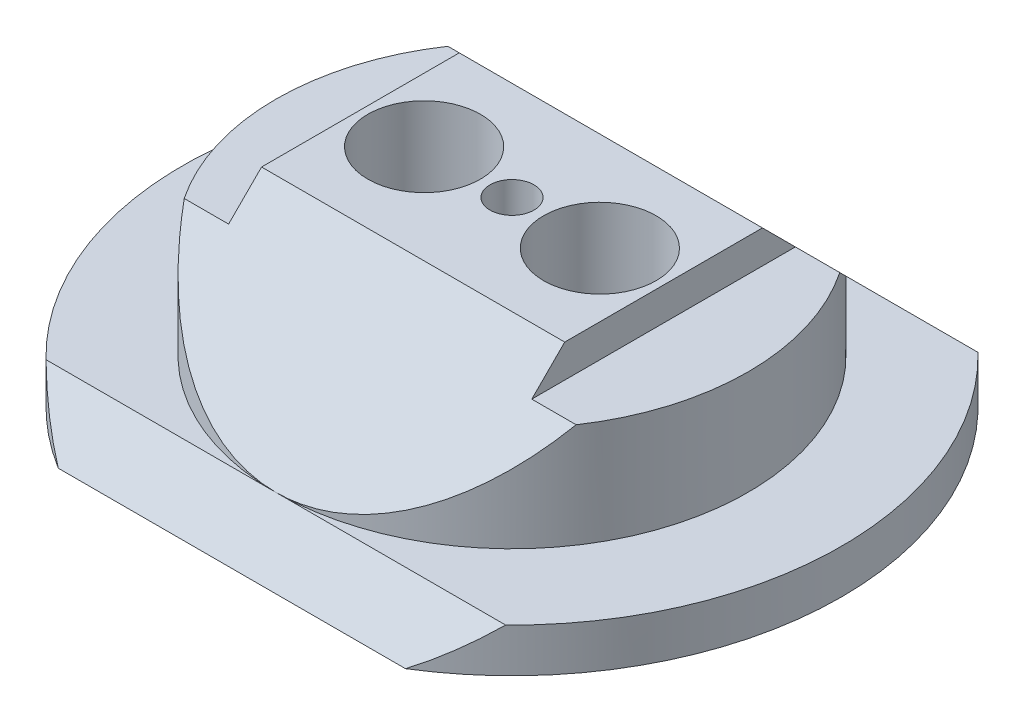
SolidWorks part; units mm, degrees
ref_plane "Front Plane" through (0, 0, 0) normal (0, 0, 1) x (1, 0, 0)
ref_plane "Top Plane" through (0, 0, 0) normal (0, 1, 0) x (1, 0, 0)
ref_plane "Right Plane" through (0, 0, 0) normal (1, 0, 0) x (0, 0, -1)
sketch "Sketch1" plane through (0, 0, 0) normal (0, 1, 0) x (1, 0, 0)
  circle A0 centre (0, 0) radius 30
extrude "Boss-Extrude1" add sketch "Sketch1" along normal blind 4
sketch "Sketch2" plane through (0, 0, 0) normal (1, 0, 0) x (0, 0, -1)
  line L0 (0, 4) -> (21.5, 4)
  line L1 (30, 4) -> (-30, 4) construction
  line L3 (0, 4) -> (-21.5, 4)
  line L5 (0, 4) -> (0, 19.5) construction
  line L6 (-9, 16.5) -> (-21.5, 4)
  line L7 (-9, 16.5) -> (9, 16.5)
  line L9 (9, 16.5) -> (21.5, 4)
  dimension "D1" = 12.5
  dimension "D2" = 45
  dimension "D3" = 21.5
  dimension "D4" = 21.5
  dimension "D5" = 45
sketch "Sketch3" plane through (0, 4, 0) normal (0, 1, 0) x (1, 0, 0)
  circle A0 centre (0, 0) radius 21.5
  dimension "D1" = 43
extrude "Boss-Extrude2" add sketch "Sketch2" along normal up to surface and the other way up to surface up to face at (0, 4, 30) other way up to face at (0, 4, 30)
ref_plane "Plane1" through (0, 12.75, -12.75) normal (0, 0.7071, -0.7071) x (1, 0, 0)
other "SurfaceCut1"
ref_plane "Plane2" through (0, 12.75, 12.75) normal (0, 0.7071, 0.7071) x (1, 0, 0)
other "SurfaceCut2"
extrude "Cut-Extrude2" cut sketch "Sketch3" against normal up to surface (12.5 mm away) flip side to cut contours A0
sketch "Sketch5" plane through (0, 0, 0) normal (0, -1, 0) x (-1, 0, 0)
  line L0 (0, 0) -> (0, -6)
  line L1 (0, -6) -> (-17.5, -6)
  line L2 (-17.5, -6) -> (-17.5, 6)
  line L3 (-17.5, 6) -> (17.5, 6)
  line L4 (17.5, 6) -> (17.5, -6)
  line L5 (17.5, -6) -> (0, -6)
  circle A0 centre (0, 0) radius 6
  circle A1 centre (0, 0) radius 3.5
  dimension "D1" = 12
  dimension "D2" = 7
  dimension "D3" = 12
  dimension "D4" = 6
  dimension "D5" = 35
  dimension "D6" = 17.5
extrude "Boss-Extrude3" add sketch "Sketch5" along normal blind 18 contours L1 L2 L3 L4 L5
sketch "Sketch6" plane through (0, 0, 0) normal (0, -1, 0) x (1, 0, 0)
  line L0 (0, 6) -> (0, 15) construction
  line L1 (-17.5, 6) -> (17.5, 6) construction
  line L2 (0, 15) -> (7, 15)
  line L3 (7, 15) -> (7, 6)
  line L4 (-17.5, 6) -> (17.5, 6) construction
  line L5 (7, 6) -> (-7, 6)
  line L6 (-7, 6) -> (-7, 15)
  line L7 (-7, 15) -> (0, 15)
  dimension "D1" = 14
  dimension "D2" = 9
extrude "Boss-Extrude4" add sketch "Sketch6" along normal blind 15 contours L7 L2 L3 L5 L6
sketch "Sketch7" plane through (0, 0, 0) normal (0, -1, 0) x (1, 0, 0)
  line L0 (0, -6) -> (0, -15) construction
  line L1 (17.5, -6) -> (-17.5, -6) construction
  line L2 (0, -15) -> (7, -15)
  line L3 (7, -15) -> (7, -6)
  line L4 (7, -6) -> (-7, -6)
  line L7 (-7, -6) -> (-7, -15)
  line L8 (-7, -15) -> (0, -15)
  dimension "D1" = 9
  dimension "D2" = 14
extrude "Boss-Extrude5" add sketch "Sketch7" along normal blind 15
sketch "Sketch8" plane through (0, 0, 0) normal (0, 0, 1) x (1, 0, 0)
  line L0 (0, 0) -> (12.5, 0) construction
  line L1 (12.5, 0) -> (12.5, -12.5) construction
  line L2 (12.5, -12.5) -> (-12.5, -12.5) construction
  line L3 (-12.5, -12.5) -> (-12.5, 0) construction
  line L4 (-12.5, 0) -> (0, 0) construction
  circle A0 centre (-12.5, -12.5) radius 2
  circle A1 centre (12.5, -12.5) radius 2
  dimension "D4" = 4
  dimension "D5" = 4
  dimension "D1" = 12.5
  dimension "D2" = 25
  dimension "D3" = 12.5
extrude "Cut-Extrude3" cut sketch "Sketch8" against normal through all both and the other way through all contours A0 | A1
ref_plane "Plane3" through (0, -18, 0) normal (0, -1, 0) x (-1, 0, 0)
ref_plane "Plane4" through (10.366, -9.6749, -8.0624) normal (0.6355, -0.5931, -0.4943) x (-0.3613, 0.3373, -0.8693)
ref_plane "Plane5" through (-10.366, -9.6749, -8.0624) normal (0.6355, 0.5931, 0.4943) x (0.3613, 0.3373, -0.8693)
ref_plane "Plane6" through (10.366, -9.6749, 8.0624) normal (-0.6355, 0.5931, -0.4943) x (-0.3613, 0.3373, 0.8693)
ref_plane "Plane7" through (-10.366, -9.6749, 8.0624) normal (0.6355, 0.5931, -0.4943) x (-0.3613, -0.3373, -0.8693)
ref_plane "Plane9" through (0, 0, 6) normal (0, 0, 1) x (1, 0, 0)
sketch "Sketch16" plane through (0, 0, 6) normal (0, 0, 1) x (1, 0, 0)
  line L0 (17.5, -18) -> (17.5, -14.5)
  line L1 (-6.6, -18) -> (6.6, -18) construction
  line L2 (17.5, -18) -> (17.5, 0) construction
  line L3 (17.5, -18) -> (14, -18)
  line L4 (17.5, -14.5) -> (14, -18)
  line L5 (-17.5, -18) -> (-14, -18)
  line L6 (-17.5, -18) -> (-17.5, 0) construction
  line L7 (-14, -18) -> (-17.5, -14.5)
  line L8 (-17.5, -14.5) -> (-17.5, -18)
  dimension "D2" = 3.5
extrude "Cut-Extrude8" cut sketch "Sketch16" against normal through all both and the other way through all
sketch "Sketch17" plane through (10.366, -9.6749, -8.0624) normal (0.6355, -0.5931, -0.4943) x (-0.3613, 0.3373, -0.8693)
  line L0 (-2.3725, -6.1896) -> (7.9806, -0.7067)
  line L1 (5.4512, -6.1896) -> (10.5101, 4.7762) construction
  line L2 (7.9806, -0.7067) -> (7.9806, -10.9658)
  line L3 (10.5101, -15.7421) -> (5.4512, -6.1896) construction
  line L4 (7.9806, -10.9658) -> (-2.3725, -6.1896)
extrude "Cut-Extrude9" cut sketch "Sketch17" along normal through all
sketch "Sketch19" plane through (-10.366, -9.6749, -8.0624) normal (0.6355, 0.5931, 0.4943) x (0.3613, 0.3373, -0.8693)
  line L0 (-2.3725, -6.1896) -> (7.9806, -10.9658)
  line L1 (7.9806, -10.9658) -> (7.9806, -0.7067)
  line L2 (5.4512, -6.1896) -> (10.5101, 4.7762) construction
  line L3 (7.9806, -0.7067) -> (-2.3725, -6.1896)
extrude "Cut-Extrude11" cut sketch "Sketch19" against normal blind 20 contours L3 L0 L1
sketch "Sketch20" plane through (-10.366, -9.6749, 8.0624) normal (0.6355, 0.5931, -0.4943) x (-0.3613, -0.3373, -0.8693)
  line L0 (2.3725, -6.1896) -> (-7.9806, -0.7067)
  line L1 (-5.4512, -6.1896) -> (-10.5101, 4.7762) construction
  line L2 (-7.9806, -0.7067) -> (-7.9806, -10.9658)
  line L3 (-5.4512, -6.1896) -> (-10.5101, -15.7421) construction
  line L4 (-7.9806, -10.9658) -> (2.3725, -6.1896)
extrude "Cut-Extrude12" cut sketch "Sketch20" against normal blind 20
sketch "Sketch21" plane through (10.366, -9.6749, 8.0624) normal (-0.6355, 0.5931, -0.4943) x (-0.3613, 0.3373, 0.8693)
  line L0 (-2.3725, -6.1896) -> (7.9806, -0.7067)
  line L1 (5.4512, -6.1896) -> (10.5101, 4.7762) construction
  line L2 (7.9806, -0.7067) -> (7.9806, -10.9658)
  line L3 (7.9806, -10.9658) -> (-2.3725, -6.1896)
extrude "Cut-Extrude13" cut sketch "Sketch21" against normal blind 20 contours L0 L2 L3
ref_plane "Plane10" through (0, 16.5, 0) normal (0, 1, 0) x (1, 0, 0)
sketch "Sketch25" plane through (0, 0, 0) normal (0, 0, 1) x (1, 0, 0)
  line L1 (-33.0377, 0) -> (33.0377, 0)
  line L2 (-33.0377, 0) -> (-33.0377, -20.1422)
  line L3 (-33.0377, -20.1422) -> (33.0377, -20.1422)
  line L4 (33.0377, 0) -> (33.0377, -20.1422)
  dimension "D1" = 20.1422
  dimension "D2" = 66.0754
extrude "Cut-Extrude14" cut sketch "Sketch25" along normal through all both and the other way through all
sketch "Sketch26" plane through (0, 16.5, 0) normal (0, 1, 0) x (1, 0, 0)
  line L0 (-9.075, 0) -> (9.075, 0) construction
  circle A0 centre (-8, 0) radius 5.125
  circle A2 centre (8, 0) radius 5.125
  dimension "D1" = 10.25
  dimension "D2" = 10.25
  dimension "D3" = 8
  dimension "D4" = 8
extrude "Cut-Extrude15" cut sketch "Sketch26" against normal blind 24
sketch "Sketch29" plane through (0, 0, 6) normal (0, 0, 1) x (1, 0, 0)
  line L0 (21.5, 4) -> (21.5, 16.5) construction
  line L1 (21.5, 13.5) -> (13.8, 13.5)
  line L2 (21.5, 13.5) -> (21.5, 16.5)
  line L3 (21.5, 16.5) -> (13.8, 16.5)
  line L4 (13.8, 13.5) -> (13.8, 16.5)
  line L5 (9.9, 16.5) -> (-9.9, 16.5) construction
  dimension "D1" = 3
  dimension "D2" = 7.7
extrude "Cut-Extrude17" cut sketch "Sketch29" against normal through all both and the other way through all
sketch "Sketch31" plane through (0, 0, 6) normal (0, 0, 1) x (1, 0, 0)
  line L0 (-21.5, 16.5) -> (-21.5, 4) construction
  line L1 (-21.5, 13.5) -> (-13.8, 13.5)
  line L2 (-21.5, 13.5) -> (-21.5, 16.5)
  line L3 (-21.5, 16.5) -> (-13.8, 16.5)
  line L4 (-13.8, 13.5) -> (-13.8, 16.5)
  line L5 (9.9, 16.5) -> (-9.9, 16.5) construction
  dimension "D1" = 3
  dimension "D2" = 7.7
extrude "Cut-Extrude18" cut sketch "Sketch31" against normal through all both and the other way through all
sketch "Sketch34" plane through (0, 0, 0) normal (0, -1, 0) x (1, 0, 0)
  circle A0 centre (0, 0) radius 1.375
  dimension "D1" = 2.75
extrude "Cut-Extrude21" cut sketch "Sketch34" against normal blind 20
sketch "Sketch35" plane through (0, 16.5, 0) normal (0, 1, 0) x (1, 0, 0)
  circle A0 centre (0, 0) radius 2
  dimension "D1" = 4
extrude "Cut-Extrude22" cut sketch "Sketch35" against normal blind 6
sketch "Sketch37" plane through (0, 0, 0) normal (0, -1, 0) x (1, 0, 0)
  line L0 (0, -9.075) -> (0, 9.075) construction
  line L1 (9.075, 0) -> (-9.075, 0) construction
  circle A0 centre (0, -15) radius 5
  circle A1 centre (0, 15) radius 5
  circle A2 centre (-22, 0) radius 5
  circle A3 centre (22, 0) radius 5
  circle A4 centre (-14, 12) radius 5
  circle A5 centre (14, 12) radius 5
  circle A6 centre (-14, -12) radius 5
  circle A7 centre (14, -12) radius 5
  dimension "D1" = 10
  dimension "D2" = 10
  dimension "D3" = 10
  dimension "D4" = 10
  dimension "D10" = 10
  dimension "D14" = 10
  dimension "D15" = 10
  dimension "D16" = 10
  dimension "D5" = 15
  dimension "D6" = 15
  dimension "D7" = 22
  dimension "D8" = 22
  dimension "D9" = 14
  dimension "D11" = 12
  dimension "D12" = 12
  dimension "D13" = 14
  dimension "D17" = 12
  dimension "D18" = 14
  dimension "D19" = 14
  dimension "D20" = 12
extrude "Cut-Extrude23" cut sketch "Sketch37" against normal blind 3
